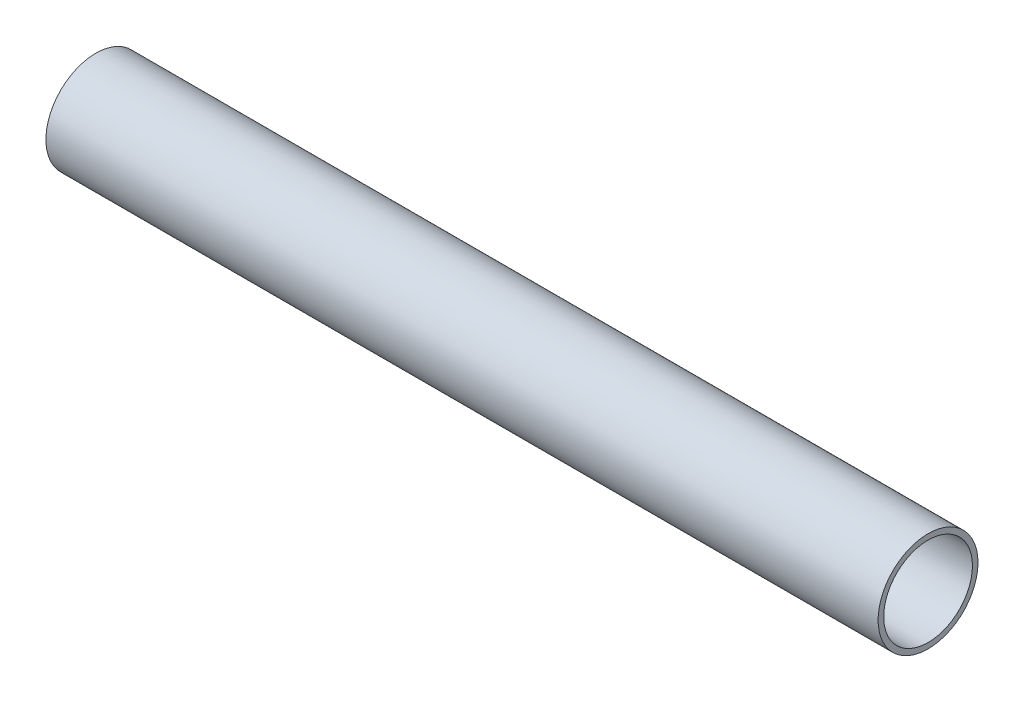
SolidWorks part; units mm, degrees
material "Kupfer"
ref_plane "Ebene vorne" through (0, 0, 0) normal (0, 0, 1) x (1, 0, 0)
ref_plane "Ebene oben" through (0, 0, 0) normal (0, 1, 0) x (1, 0, 0)
ref_plane "Ebene rechts" through (0, 0, 0) normal (1, 0, 0) x (0, 0, -1)
sketch "Skizze1" plane through (0, 0, 0) normal (1, 0, 0) x (0, 0, -1)
  circle A0 centre (0, 0) radius 9
  circle A1 centre (0, 0) radius 8
  dimension "D1" = 18
  dimension "D2" = 1
extrude "Aufsatz-Linear austragen1" add sketch "Skizze1" along normal blind 150
